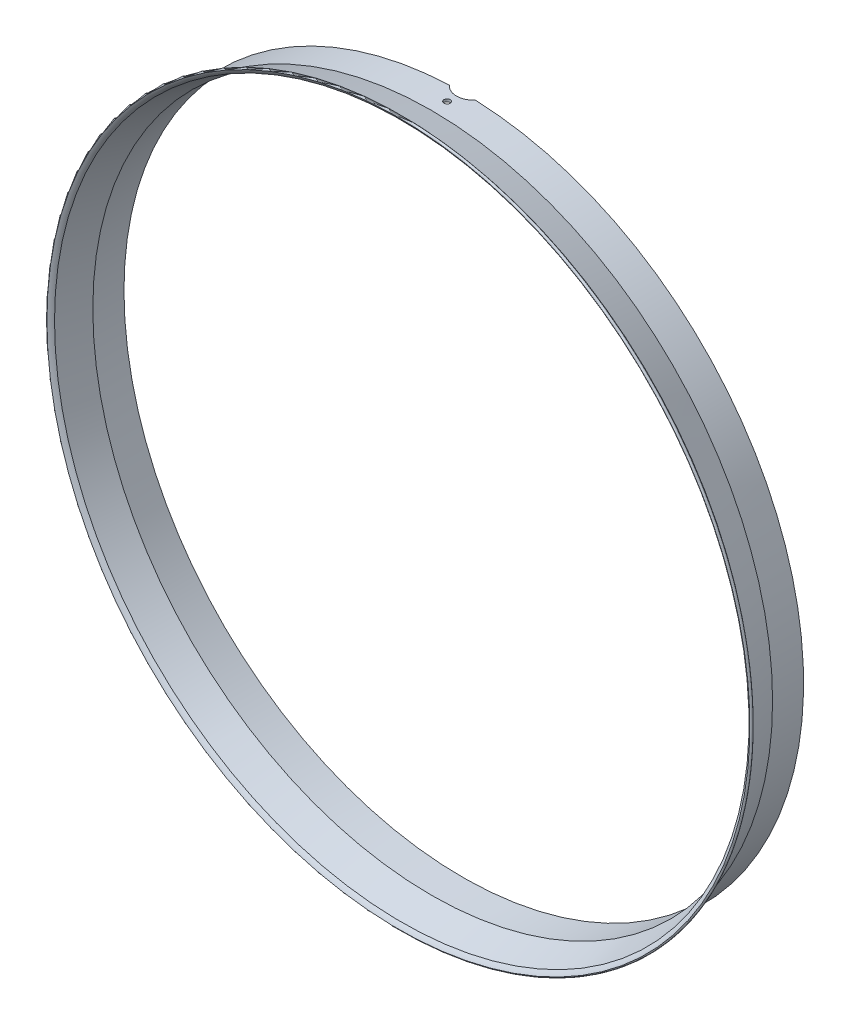
SolidWorks part; units mm, degrees
ref_plane "Front Plane" through (0, 0, 0) normal (0, 0, 1) x (1, 0, 0)
ref_plane "Top Plane" through (0, 0, 0) normal (0, 1, 0) x (1, 0, 0)
ref_plane "Right Plane" through (0, 0, 0) normal (1, 0, 0) x (0, 0, -1)
ref_plane "Plane1" through (-300, 0, 0) normal (-1, 0, 0) x (0, -1, 0)
sketch "Sketch1" plane through (-300, 0, 0) normal (-1, 0, 0) x (0, -1, 0)
  line L0 (-631.5852, -424.5263) -> (-635.7852, -438.7135)
  line L1 (-635.7852, -438.7135) -> (-635.7852, -453.67)
  line L2 (-635.7852, -453.67) -> (-634.5852, -453.67)
  line L3 (-634.5852, -453.67) -> (-634.5852, -438.7854)
  line L4 (-634.5852, -438.7854) -> (-630.5827, -425.2654)
  line L5 (-798.2852, -417.2643) -> (-798.2852, -453.67) construction
  arc A0 (-629.2508, -424.1352) -> (-630.5827, -425.2654) centre (-626.8608, -428.3017) ccw
  arc A1 (-629.5713, -422.8955) -> (-629.2508, -424.1352) centre (-629.6814, -423.5853) cw
  arc A2 (-631.5852, -424.5263) -> (-629.5713, -422.8955) centre (-626.8608, -428.3017) cw
  point P0 (-629.6814, -423.5853)
  point P13 (0, 0)
  point P14 (-628.175, -423.6143)
  dimension "D1" = 162.5
  dimension "D2" = 166.7
  dimension "D3" = 1.2
revolve "Revolve1" add sketch "Sketch1" angle 360 about L5
ref_plane "Plane2" [suppressed] through (-161.5152, 0, 0) normal (-1, 0, 0) x (0, 0, 1)
hole_wizard "Ø3.0 (3) Diameter Hole1" [suppressed] positions "Sketch3" profile "Sketch2" hole size "Ø3.0" standard "ANSI Metric"
sketch "Sketch3" [suppressed] plane through (-161.5152, 0, 0) normal (-1, 0, 0) x (0, 0, 1)
  point P0 (-369.3577, 667.332)
sketch "Sketch2" plane through (-161.5152, 667.332, -369.3577) normal (0, 1, 0) x (0, 0, -1)
  line L0 (0, 0) -> (0, 313.3874)
  line L1 (0, 313.3874) -> (1.5, 313.3874)
  line L2 (1.5, 313.3874) -> (1.5, 0)
  line L5 (1.5, 0) -> (0, 0)
  line L11 (0, -6.35) -> (0, 107.95) construction
  dimension "Thru Hole Dia." = 3
  dimension "Thru Hole Depth" = 313.3874
ref_plane "Plane3" [suppressed] through (-294.6382, 510.3284, 0) normal (-0.5, 0.866, 0) x (0.866, 0.5, 0)
hole_wizard "Ø2.5 (2.5) Diameter Hole1" [suppressed] positions "Sketch5" profile "Sketch4" hole size "Ø2.5" standard "ANSI Metric"
sketch "Sketch5" [suppressed] plane through (-294.6382, 510.3284, 0) normal (-0.5, 0.866, 0) x (0.866, 0.5, 0)
  point P0 (73.8584, 362.3577)
sketch "Sketch4" plane through (-230.675, 547.2576, -362.3577) normal (0, 0, 1) x (-0.866, -0.5, 0)
  line L0 (0, 0) -> (0, 60.0822)
  line L1 (0, 60.0822) -> (1.25, 60.0822)
  line L2 (1.25, 60.0822) -> (1.25, 0)
  line L5 (1.25, 0) -> (0, 0)
  line L11 (0, -6.35) -> (0, 107.95) construction
  dimension "Thru Hole Dia." = 2.5
  dimension "Thru Hole Depth" = 60.0822
ref_plane "Plane4" [suppressed] through (283.9418, 491.8017, 0) normal (0.5, 0.866, 0) x (0.866, -0.5, 0)
hole_wizard "Ø2.5 (2.5) Diameter Hole2" [suppressed] positions "Sketch7" profile "Sketch6" hole size "Ø2.5" standard "ANSI Metric"
sketch "Sketch7" [suppressed] plane through (283.9418, 491.8017, 0) normal (0.5, 0.866, 0) x (0.866, -0.5, 0)
  point P0 (-593.4736, 362.3577)
sketch "Sketch6" plane through (-230.0214, 788.5385, -362.3577) normal (0, 0, 1) x (-0.866, 0.5, 0)
  line L0 (0, 0) -> (0, 262.0058)
  line L1 (0, 262.0058) -> (1.25, 262.0058)
  line L2 (1.25, 262.0058) -> (1.25, 0)
  line L5 (1.25, 0) -> (0, 0)
  line L11 (0, -6.35) -> (0, 107.95) construction
  dimension "Thru Hole Dia." = 2.5
  dimension "Thru Hole Depth" = 262.0058
ref_plane "Plane5" through (0, 0, -422.8955) normal (0, 0, 1) x (1, 0, 0)
ref_point "Point1"
ref_plane "Plane6" through (0, 798.2852, 0) normal (0, 1, 0) x (1, 0, 0)
sketch "Sketch8" plane through (0, 798.2852, 0) normal (0, 1, 0) x (1, 0, 0)
  line L0 (-300, 407.7468) -> (-300, 499.5932) construction
  line L3 (-293.8087, 453.67) -> (-306.1913, 453.67)
  line L5 (-137.5, 453.67) -> (-462.5, 453.67) construction
  line L6 (-136.3, 453.67) -> (-463.7, 453.67) construction
  line L7 (-300, 472.8955) -> (-300, 372.8955) construction
  arc A0 (-306.1913, 453.67) -> (-293.8087, 453.67) centre (-300, 458.7364) ccw
  circle A1 centre (-300, 446.2364) radius 1.5
  point P4 (0, 0)
  point P9 (-300, 453.67)
  dimension "D1" = 8
  dimension "D2" = 12.5
  dimension "D3" = 3
extrude "Cut-Extrude1" cut sketch "Sketch8" along normal through all
